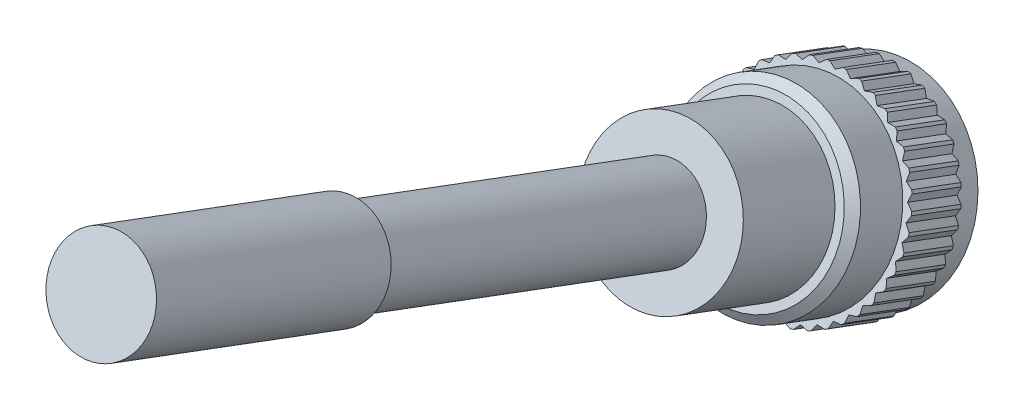
SolidWorks part; units mm, degrees
ref_plane "Plan de face" through (0, 0, 0) normal (0, 0, 1) x (1, 0, 0)
ref_plane "Plan de dessus" through (0, 0, 0) normal (0, 1, 0) x (1, 0, 0)
ref_plane "Plan de droite" through (0, 0, 0) normal (1, 0, 0) x (0, 0, -1)
ref_plane "Plan1" through (0, -2.1562, 0.8961) normal (0, -0.9234, 0.3838) x (1, 0, 0)
sketch "Esquisse1" plane through (0, -2.1562, 0.8961) normal (0, -0.9234, 0.3838) x (1, 0, 0)
  line L0 (-42.9845, 116.5438) -> (-48.973, 116.916)
  line L1 (-48.973, 116.916) -> (-49.1901, 113.4227)
  line L2 (-49.1901, 113.4227) -> (-43.2016, 113.0506)
  line L3 (-43.2016, 113.0506) -> (-42.9845, 116.5438)
  line L4 (-48.95, 117.2866) -> (-49.2131, 113.052) construction
revolve "Révolution1" add sketch "Esquisse1" angle 360 about L4
sketch "Esquisse2" plane through (7.0488, 43.5316, 104.7495) normal (0.062, 0.383, 0.9217) x (0.9981, -0.0238, -0.0573)
  line L0 (-57.5874, 3.4853) -> (-57.1753, 3.3192)
  line L1 (-57.1753, 3.3192) -> (-56.8499, 3.6217)
  arc A0 (-56.8499, 3.6217) -> (-57.5874, 3.4853) centre (-56.1298, -2.335) ccw
extrude "Enlèv. mat.-Extru.1" cut sketch "Esquisse2" against normal blind 3.5
sketch "Esquisse3" plane through (7.0488, 43.5316, 104.7495) normal (0.062, 0.383, 0.9217) x (0.9981, -0.0238, -0.0573)
  line L0 (-56.659, 3.6417) -> (-56.2779, 3.4131)
  line L1 (-56.2779, 3.4131) -> (-55.9092, 3.661)
  arc A0 (-55.9092, 3.661) -> (-56.659, 3.6417) centre (-56.1298, -2.335) ccw
extrude "Enlèv. mat.-Extru.2" cut sketch "Esquisse3" against normal blind 3.5
sketch "Esquisse4" plane through (7.0488, 43.5316, 104.7495) normal (0.062, 0.383, 0.9217) x (0.9981, -0.0238, -0.0573)
  line L0 (-55.7175, 3.6509) -> (-55.3769, 3.3655)
  line L1 (-55.3769, 3.3655) -> (-54.974, 3.5527)
  arc A0 (-54.974, 3.5527) -> (-55.7175, 3.6509) centre (-56.1298, -2.335) ccw
extrude "Enlèv. mat.-Extru.3" cut sketch "Esquisse4" against normal blind 3.5
sketch "Esquisse5" plane through (7.0488, 43.5316, 104.7495) normal (0.062, 0.383, 0.9217) x (0.9981, -0.0238, -0.0573)
  line L0 (-54.7862, 3.5127) -> (-54.4944, 3.1776)
  line L1 (-54.4944, 3.1776) -> (-54.0672, 3.2994)
  arc A0 (-54.0672, 3.2994) -> (-54.7862, 3.5127) centre (-56.1298, -2.335) ccw
extrude "Enlèv. mat.-Extru.4" cut sketch "Esquisse5" against normal blind 3.5
sketch "Esquisse6" plane through (7.0488, 43.5316, 104.7495) normal (0.062, 0.383, 0.9217) x (0.9981, -0.0238, -0.0573)
  line L0 (-53.888, 3.2305) -> (-53.6522, 2.8539)
  line L1 (-53.6522, 2.8539) -> (-53.2111, 2.9073)
  arc A0 (-53.2111, 2.9073) -> (-53.888, 3.2305) centre (-56.1298, -2.335) ccw
extrude "Enlèv. mat.-Extru.5" cut sketch "Esquisse6" against normal blind 3.5
sketch "Esquisse7" plane through (7.0488, 43.5316, 104.7495) normal (0.062, 0.383, 0.9217) x (0.9981, -0.0238, -0.0573)
  line L0 (-53.0449, 2.8113) -> (-52.871, 2.4024)
  line L1 (-52.871, 2.4024) -> (-52.427, 2.3862)
  arc A0 (-52.427, 2.3862) -> (-53.0449, 2.8113) centre (-56.1298, -2.335) ccw
extrude "Enlèv. mat.-Extru.6" cut sketch "Esquisse7" against normal blind 3.5
sketch "Esquisse8" plane through (7.0488, 43.5316, 104.7495) normal (0.062, 0.383, 0.9217) x (0.9981, -0.0238, -0.0573)
  line L0 (-52.2779, 2.2653) -> (-52.17, 1.8343)
  line L1 (-52.17, 1.8343) -> (-51.734, 1.7488)
  arc A0 (-51.734, 1.7488) -> (-52.2779, 2.2653) centre (-56.1298, -2.335) ccw
extrude "Enlèv. mat.-Extru.7" cut sketch "Esquisse8" against normal blind 3.5
sketch "Esquisse9" plane through (7.0488, 43.5316, 104.7495) normal (0.062, 0.383, 0.9217) x (0.9981, -0.0238, -0.0573)
  line L0 (-51.6056, 1.6061) -> (-51.5666, 1.1635)
  line L1 (-51.5666, 1.1635) -> (-51.1493, 1.0109)
  arc A0 (-51.1493, 1.0109) -> (-51.6056, 1.6061) centre (-56.1298, -2.335) ccw
extrude "Enlèv. mat.-Extru.8" cut sketch "Esquisse9" against normal blind 3.5
sketch "Esquisse10" plane through (7.0488, 43.5316, 104.7495) normal (0.062, 0.383, 0.9217) x (0.9981, -0.0238, -0.0573)
  line L0 (-51.0448, 0.8499) -> (-51.0755, 0.4066)
  line L1 (-51.0755, 0.4066) -> (-50.6872, 0.1906)
  arc A0 (-50.6872, 0.1906) -> (-51.0448, 0.8499) centre (-56.1298, -2.335) ccw
extrude "Enlèv. mat.-Extru.9" cut sketch "Esquisse10" against normal blind 3.5
sketch "Esquisse11" plane through (7.0488, 43.5316, 104.7495) normal (0.062, 0.383, 0.9217) x (0.9981, -0.0238, -0.0573)
  line L0 (-50.6092, 0.0152) -> (-50.7088, -0.4178)
  line L1 (-50.7088, -0.4178) -> (-50.3591, -0.6919)
  arc A0 (-50.3591, -0.6919) -> (-50.6092, 0.0152) centre (-56.1298, -2.335) ccw
extrude "Enlèv. mat.-Extru.10" cut sketch "Esquisse11" against normal blind 3.5
sketch "Esquisse12" plane through (7.0488, 43.5316, 104.7495) normal (0.062, 0.383, 0.9217) x (0.9981, -0.0238, -0.0573)
  line L0 (-50.3095, -0.8774) -> (-50.4756, -1.2894)
  line L1 (-50.4756, -1.2894) -> (-50.1732, -1.6149)
  arc A0 (-50.1732, -1.6149) -> (-50.3095, -0.8774) centre (-56.1298, -2.335) ccw
extrude "Enlèv. mat.-Extru.11" cut sketch "Esquisse12" against normal blind 3.5
sketch "Esquisse13" plane through (7.0488, 43.5316, 104.7495) normal (0.062, 0.383, 0.9217) x (0.9981, -0.0238, -0.0573)
  line L0 (-50.1532, -1.8058) -> (-50.3817, -2.1868)
  line L1 (-50.3817, -2.1868) -> (-50.1338, -2.5555)
  arc A0 (-50.1338, -2.5555) -> (-50.1532, -1.8058) centre (-56.1298, -2.335) ccw
extrude "Enlèv. mat.-Extru.12" cut sketch "Esquisse13" against normal blind 3.5
sketch "Esquisse14" plane through (7.0488, 43.5316, 104.7495) normal (0.062, 0.383, 0.9217) x (0.9981, -0.0238, -0.0573)
  line L0 (-50.144, -2.7473) -> (-50.4293, -3.0878)
  line L1 (-50.4293, -3.0878) -> (-50.2422, -3.4908)
  arc A0 (-50.2422, -3.4908) -> (-50.144, -2.7473) centre (-56.1298, -2.335) ccw
extrude "Enlèv. mat.-Extru.13" cut sketch "Esquisse14" against normal blind 3.5
sketch "Esquisse15" plane through (7.0488, 43.5316, 104.7495) normal (0.062, 0.383, 0.9217) x (0.9981, -0.0238, -0.0573)
  line L0 (-50.2822, -3.6786) -> (-50.6173, -3.9703)
  line L1 (-50.6173, -3.9703) -> (-50.4955, -4.3976)
  arc A0 (-50.4955, -4.3976) -> (-50.2822, -3.6786) centre (-56.1298, -2.335) ccw
extrude "Enlèv. mat.-Extru.14" cut sketch "Esquisse15" against normal blind 3.5
sketch "Esquisse16" plane through (7.0488, 43.5316, 104.7495) normal (0.062, 0.383, 0.9217) x (0.9981, -0.0238, -0.0573)
  line L0 (-50.5643, -4.5768) -> (-50.9409, -4.8125)
  line L1 (-50.9409, -4.8125) -> (-50.8875, -5.2536)
  arc A0 (-50.8875, -5.2536) -> (-50.5643, -4.5768) centre (-56.1298, -2.335) ccw
extrude "Enlèv. mat.-Extru.15" cut sketch "Esquisse16" against normal blind 3.5
sketch "Esquisse17" plane through (7.0488, 43.5316, 104.7495) normal (0.062, 0.383, 0.9217) x (0.9981, -0.0238, -0.0573)
  line L0 (-50.9836, -5.4198) -> (-51.3924, -5.5937)
  line L1 (-51.3924, -5.5937) -> (-51.4086, -6.0377)
  arc A0 (-51.4086, -6.0377) -> (-50.9836, -5.4198) centre (-56.1298, -2.335) ccw
extrude "Enlèv. mat.-Extru.16" cut sketch "Esquisse17" against normal blind 3.5
sketch "Esquisse18" plane through (7.0488, 43.5316, 104.7495) normal (0.062, 0.383, 0.9217) x (0.9981, -0.0238, -0.0573)
  line L0 (-51.5295, -6.1869) -> (-51.9605, -6.2947)
  line L1 (-51.9605, -6.2947) -> (-52.046, -6.7307)
  arc A0 (-52.046, -6.7307) -> (-51.5295, -6.1869) centre (-56.1298, -2.335) ccw
extrude "Enlèv. mat.-Extru.17" cut sketch "Esquisse18" against normal blind 3.5
sketch "Esquisse19" plane through (7.0488, 43.5316, 104.7495) normal (0.062, 0.383, 0.9217) x (0.9981, -0.0238, -0.0573)
  line L0 (-52.1887, -6.8591) -> (-52.6313, -6.8982)
  line L1 (-52.6313, -6.8982) -> (-52.7839, -7.3154)
  arc A0 (-52.7839, -7.3154) -> (-52.1887, -6.8591) centre (-56.1298, -2.335) ccw
extrude "Enlèv. mat.-Extru.18" cut sketch "Esquisse19" against normal blind 3.5
sketch "Esquisse20" plane through (7.0488, 43.5316, 104.7495) normal (0.062, 0.383, 0.9217) x (0.9981, -0.0238, -0.0573)
  line L0 (-52.945, -7.4199) -> (-53.3882, -7.3893)
  line L1 (-53.3882, -7.3893) -> (-53.6042, -7.7775)
  arc A0 (-53.6042, -7.7775) -> (-52.945, -7.4199) centre (-56.1298, -2.335) ccw
extrude "Enlèv. mat.-Extru.19" cut sketch "Esquisse20" against normal blind 3.5
sketch "Esquisse21" plane through (7.0488, 43.5316, 104.7495) normal (0.062, 0.383, 0.9217) x (0.9981, -0.0238, -0.0573)
  line L0 (-53.7796, -7.8555) -> (-54.2126, -7.7559)
  line L1 (-54.2126, -7.7559) -> (-54.4867, -8.1056)
  arc A0 (-54.4867, -8.1056) -> (-53.7796, -7.8555) centre (-56.1298, -2.335) ccw
extrude "Enlèv. mat.-Extru.20" cut sketch "Esquisse21" against normal blind 3.5
sketch "Esquisse22" plane through (7.0488, 43.5316, 104.7495) normal (0.062, 0.383, 0.9217) x (0.9981, -0.0238, -0.0573)
  line L0 (-54.6722, -8.1552) -> (-55.0843, -7.9891)
  line L1 (-55.0843, -7.9891) -> (-55.4097, -8.2916)
  arc A0 (-55.4097, -8.2916) -> (-54.6722, -8.1552) centre (-56.1298, -2.335) ccw
extrude "Enlèv. mat.-Extru.21" cut sketch "Esquisse22" against normal blind 3.5
sketch "Esquisse23" plane through (7.0488, 43.5316, 104.7495) normal (0.062, 0.383, 0.9217) x (0.9981, -0.0238, -0.0573)
  line L0 (-55.6006, -8.3116) -> (-55.9816, -8.083)
  line L1 (-55.9816, -8.083) -> (-56.3504, -8.3309)
  arc A0 (-56.3504, -8.3309) -> (-55.6006, -8.3116) centre (-56.1298, -2.335) ccw
extrude "Enlèv. mat.-Extru.22" cut sketch "Esquisse23" against normal blind 3.5
sketch "Esquisse24" plane through (7.0488, 43.5316, 104.7495) normal (0.062, 0.383, 0.9217) x (0.9981, -0.0238, -0.0573)
  line L0 (-56.5421, -8.3208) -> (-56.8827, -8.0355)
  line L1 (-56.8827, -8.0355) -> (-57.2856, -8.2226)
  arc A0 (-57.2856, -8.2226) -> (-56.5421, -8.3208) centre (-56.1298, -2.335) ccw
extrude "Enlèv. mat.-Extru.23" cut sketch "Esquisse24" against normal blind 3.5
sketch "Esquisse25" plane through (7.0488, 43.5316, 104.7495) normal (0.062, 0.383, 0.9217) x (0.9981, -0.0238, -0.0573)
  line L0 (-57.4734, -8.1826) -> (-57.7652, -7.8475)
  line L1 (-57.7652, -7.8475) -> (-58.1924, -7.9693)
  arc A0 (-58.1924, -7.9693) -> (-57.4734, -8.1826) centre (-56.1298, -2.335) ccw
extrude "Enlèv. mat.-Extru.24" cut sketch "Esquisse25" against normal blind 3.5
sketch "Esquisse26" plane through (7.0488, 43.5316, 104.7495) normal (0.062, 0.383, 0.9217) x (0.9981, -0.0238, -0.0573)
  line L0 (-58.3716, -7.9004) -> (-58.6074, -7.5238)
  line L1 (-58.6074, -7.5238) -> (-59.0484, -7.5772)
  arc A0 (-59.0484, -7.5772) -> (-58.3716, -7.9004) centre (-56.1298, -2.335) ccw
extrude "Enlèv. mat.-Extru.25" cut sketch "Esquisse26" against normal blind 3.5
sketch "Esquisse27" plane through (7.0488, 43.5316, 104.7495) normal (0.062, 0.383, 0.9217) x (0.9981, -0.0238, -0.0573)
  line L0 (-59.2147, -7.4812) -> (-59.3886, -7.0723)
  line L1 (-59.3886, -7.0723) -> (-59.8326, -7.0561)
  arc A0 (-59.8326, -7.0561) -> (-59.2147, -7.4812) centre (-56.1298, -2.335) ccw
extrude "Enlèv. mat.-Extru.26" cut sketch "Esquisse27" against normal blind 3.5
sketch "Esquisse28" plane through (7.0488, 43.5316, 104.7495) normal (0.062, 0.383, 0.9217) x (0.9981, -0.0238, -0.0573)
  line L0 (-59.9817, -6.9352) -> (-60.0895, -6.5042)
  line L1 (-60.0895, -6.5042) -> (-60.5255, -6.4187)
  arc A0 (-60.5255, -6.4187) -> (-59.9817, -6.9352) centre (-56.1298, -2.335) ccw
extrude "Enlèv. mat.-Extru.27" cut sketch "Esquisse28" against normal blind 3.5
sketch "Esquisse29" plane through (7.0488, 43.5316, 104.7495) normal (0.062, 0.383, 0.9217) x (0.9981, -0.0238, -0.0573)
  line L0 (-60.6539, -6.276) -> (-60.693, -5.8335)
  line L1 (-60.693, -5.8335) -> (-61.1103, -5.6808)
  arc A0 (-61.1103, -5.6808) -> (-60.6539, -6.276) centre (-56.1298, -2.335) ccw
extrude "Enlèv. mat.-Extru.28" cut sketch "Esquisse29" against normal blind 3.5
sketch "Esquisse30" plane through (7.0488, 43.5316, 104.7495) normal (0.062, 0.383, 0.9217) x (0.9981, -0.0238, -0.0573)
  line L0 (-61.2148, -5.5198) -> (-61.1841, -5.0765)
  line L1 (-61.1841, -5.0765) -> (-61.5724, -4.8605)
  arc A0 (-61.5724, -4.8605) -> (-61.2148, -5.5198) centre (-56.1298, -2.335) ccw
extrude "Enlèv. mat.-Extru.29" cut sketch "Esquisse30" against normal blind 3.5
sketch "Esquisse31" plane through (7.0488, 43.5316, 104.7495) normal (0.062, 0.383, 0.9217) x (0.9981, -0.0238, -0.0573)
  line L0 (-61.6504, -4.6851) -> (-61.5508, -4.2521)
  line L1 (-61.5508, -4.2521) -> (-61.9004, -3.978)
  arc A0 (-61.9004, -3.978) -> (-61.6504, -4.6851) centre (-56.1298, -2.335) ccw
extrude "Enlèv. mat.-Extru.30" cut sketch "Esquisse31" against normal blind 3.5
sketch "Esquisse32" plane through (7.0488, 43.5316, 104.7495) normal (0.062, 0.383, 0.9217) x (0.9981, -0.0238, -0.0573)
  line L0 (-61.9501, -3.7926) -> (-61.7839, -3.3805)
  line L1 (-61.7839, -3.3805) -> (-62.0864, -3.0551)
  arc A0 (-62.0864, -3.0551) -> (-61.9501, -3.7926) centre (-56.1298, -2.335) ccw
extrude "Enlèv. mat.-Extru.31" cut sketch "Esquisse32" against normal blind 3.5
sketch "Esquisse33" plane through (7.0488, 43.5316, 104.7495) normal (0.062, 0.383, 0.9217) x (0.9981, -0.0238, -0.0573)
  line L0 (-62.1064, -2.8641) -> (-61.8779, -2.4831)
  line L1 (-61.8779, -2.4831) -> (-62.1257, -2.1144)
  arc A0 (-62.1257, -2.1144) -> (-62.1064, -2.8641) centre (-56.1298, -2.335) ccw
extrude "Enlèv. mat.-Extru.32" cut sketch "Esquisse33" against normal blind 3.5
sketch "Esquisse34" plane through (7.0488, 43.5316, 104.7495) normal (0.062, 0.383, 0.9217) x (0.9981, -0.0238, -0.0573)
  line L0 (-62.1156, -1.9227) -> (-61.8303, -1.5821)
  line L1 (-61.8303, -1.5821) -> (-62.0174, -1.1791)
  arc A0 (-62.0174, -1.1791) -> (-62.1156, -1.9227) centre (-56.1298, -2.335) ccw
extrude "Enlèv. mat.-Extru.33" cut sketch "Esquisse34" against normal blind 3.5
sketch "Esquisse35" plane through (7.0488, 43.5316, 104.7495) normal (0.062, 0.383, 0.9217) x (0.9981, -0.0238, -0.0573)
  line L0 (-61.9774, -0.9913) -> (-61.6423, -0.6996)
  line L1 (-61.6423, -0.6996) -> (-61.7641, -0.2723)
  arc A0 (-61.7641, -0.2723) -> (-61.9774, -0.9913) centre (-56.1298, -2.335) ccw
extrude "Enlèv. mat.-Extru.34" cut sketch "Esquisse35" against normal blind 3.5
sketch "Esquisse36" plane through (7.0488, 43.5316, 104.7495) normal (0.062, 0.383, 0.9217) x (0.9981, -0.0238, -0.0573)
  line L0 (-61.6952, -0.0931) -> (-61.3186, 0.1426)
  line L1 (-61.3186, 0.1426) -> (-61.3721, 0.5837)
  arc A0 (-61.3721, 0.5837) -> (-61.6952, -0.0931) centre (-56.1298, -2.335) ccw
extrude "Enlèv. mat.-Extru.35" cut sketch "Esquisse36" against normal blind 3.5
sketch "Esquisse37" plane through (7.0488, 43.5316, 104.7495) normal (0.062, 0.383, 0.9217) x (0.9981, -0.0238, -0.0573)
  line L0 (-61.276, 0.7499) -> (-60.8672, 0.9238)
  line L1 (-60.8672, 0.9238) -> (-60.851, 1.3678)
  arc A0 (-60.851, 1.3678) -> (-61.276, 0.7499) centre (-56.1298, -2.335) ccw
extrude "Enlèv. mat.-Extru.36" cut sketch "Esquisse37" against normal blind 3.5
sketch "Esquisse38" plane through (7.0488, 43.5316, 104.7495) normal (0.062, 0.383, 0.9217) x (0.9981, -0.0238, -0.0573)
  line L0 (-60.7301, 1.517) -> (-60.2991, 1.6248)
  line L1 (-60.2991, 1.6248) -> (-60.2136, 2.0608)
  arc A0 (-60.2136, 2.0608) -> (-60.7301, 1.517) centre (-56.1298, -2.335) ccw
extrude "Enlèv. mat.-Extru.37" cut sketch "Esquisse38" against normal blind 3.5
sketch "Esquisse39" plane through (7.0488, 43.5316, 104.7495) normal (0.062, 0.383, 0.9217) x (0.9981, -0.0238, -0.0573)
  line L0 (-60.0709, 2.1892) -> (-59.6283, 2.2283)
  line L1 (-59.6283, 2.2283) -> (-59.4757, 2.6455)
  arc A0 (-59.4757, 2.6455) -> (-60.0709, 2.1892) centre (-56.1298, -2.335) ccw
extrude "Enlèv. mat.-Extru.38" cut sketch "Esquisse39" against normal blind 3.5
sketch "Esquisse40" plane through (7.0488, 43.5316, 104.7495) normal (0.062, 0.383, 0.9217) x (0.9981, -0.0238, -0.0573)
  line L0 (-59.3146, 2.75) -> (-58.8714, 2.7194)
  line L1 (-58.8714, 2.7194) -> (-58.6554, 3.1076)
  arc A0 (-58.6554, 3.1076) -> (-59.3146, 2.75) centre (-56.1298, -2.335) ccw
extrude "Enlèv. mat.-Extru.39" cut sketch "Esquisse40" against normal blind 3.5
sketch "Esquisse41" plane through (7.0488, 43.5316, 104.7495) normal (0.062, 0.383, 0.9217) x (0.9981, -0.0238, -0.0573)
  line L0 (-58.4799, 3.1856) -> (-58.047, 3.086)
  line L1 (-58.047, 3.086) -> (-57.7729, 3.4357)
  arc A0 (-57.7729, 3.4357) -> (-58.4799, 3.1856) centre (-56.1298, -2.335) ccw
extrude "Enlèv. mat.-Extru.40" cut sketch "Esquisse41" against normal blind 3.5
sketch "Esquisse42" plane through (0, -2.1562, 0.8961) normal (0, -0.9234, 0.3838) x (1, 0, 0)
  line L0 (-52.2255, 117.1181) -> (-52.6686, 117.1456) construction
  line L1 (-45.8951, 166.4481) -> (-48.973, 116.916)
  line L2 (-48.973, 116.916) -> (-43.4836, 116.5748)
  line L3 (-43.4836, 116.5748) -> (-43.2665, 120.0681)
  line L4 (-43.2665, 120.0681) -> (-44.2646, 120.1301)
  line L5 (-44.2646, 120.1301) -> (-43.8615, 126.6176)
  line L6 (-43.8615, 126.6176) -> (-45.8576, 126.7417)
  line L7 (-45.8576, 126.7417) -> (-44.4312, 149.6974)
  line L8 (-45.7949, 168.0598) -> (-48.9941, 116.5762) construction
  line L9 (-43.9321, 149.6664) -> (-42.9009, 166.262)
  line L10 (-43.9321, 149.6664) -> (-44.4312, 149.6974)
  line L11 (-42.9009, 166.262) -> (-45.8951, 166.4481)
  dimension "D1" = 11
  dimension "D2" = 9
  dimension "D3" = 3.5
  dimension "D4" = 6.5
  dimension "D5" = 5
  dimension "D6" = 23
  dimension "D7" = 3
revolve "Révolution2" add sketch "Esquisse42" angle 360 about L8
sketch "Esquisse43" plane through (0, -2.1562, 0.8961) normal (0, -0.9234, 0.3838) x (1, 0, 0)
  line L0 (-43.4511, 113.0661) -> (-49.1901, 113.4227)
  line L1 (-49.1901, 113.4227) -> (-49.3141, 111.4265)
  line L2 (-49.3141, 111.4265) -> (-43.5752, 111.0699)
  line L3 (-43.5752, 111.0699) -> (-43.4511, 113.0661)
  line L4 (-49.168, 113.7779) -> (-49.3362, 111.0713) construction
revolve "Révolution3" add sketch "Esquisse43" angle 360 about L4
chamfer "Chanfrein1" distance 0.5 angle 45 1 edges at (-48.7559, 49.1308, 109.9753)
chamfer "Chanfrein2" distance 0.5 angle 45 1 edges at (-49.3141, 45.9145, 101.5844)
